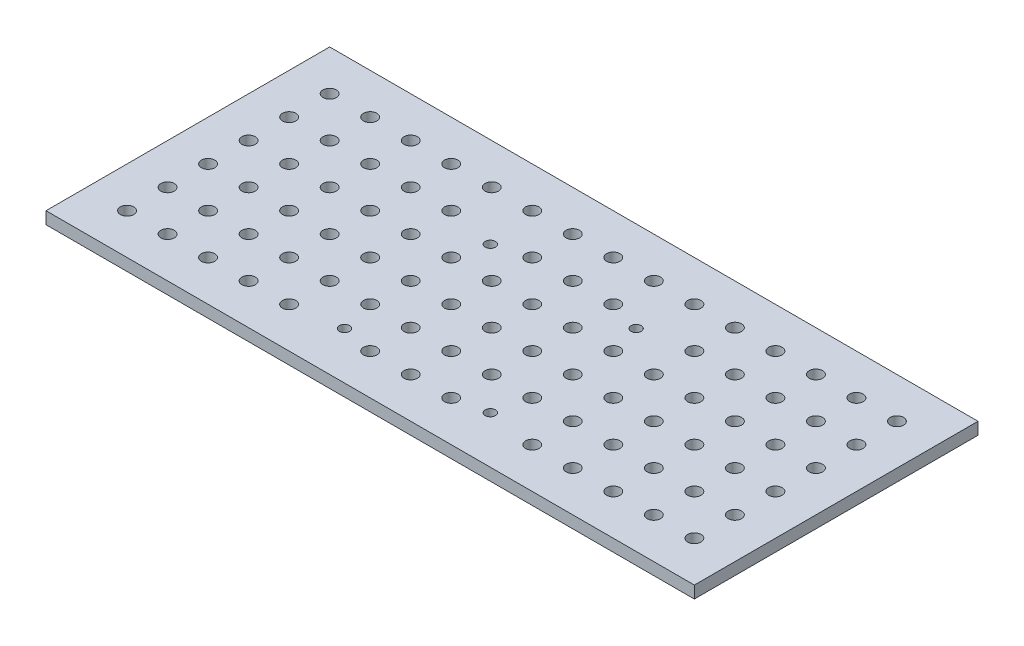
SolidWorks part; units mm, degrees
ref_plane "前视基准面" through (0, 0, 0) normal (0, 0, 1) x (1, 0, 0)
ref_plane "上视基准面" through (0, 0, 0) normal (0, 1, 0) x (1, 0, 0)
ref_plane "右视基准面" through (0, 0, 0) normal (1, 0, 0) x (0, 0, -1)
sketch "草图1" plane through (0, 0, 0) normal (0, 1, 0) x (1, 0, 0)
  line L1 (-80, -35) -> (80, -35)
  line L2 (-80, -35) -> (-80, 35)
  line L3 (-80, 35) -> (80, 35)
  line L4 (80, -35) -> (80, 35)
  line L5 (-80, -35) -> (80, 35) construction
  line L6 (-80, 35) -> (80, -35) construction
  point P0 (0, 0)
  dimension "D1" = 160
  dimension "D2" = 70
extrude "凸台-拉伸1" add sketch "草图1" along normal blind 3 contours L2 L1 L4 L3
sketch "草图2" plane through (0, 3, 0) normal (0, 1, 0) x (1, 0, 0)
  line L0 (-80, 35) -> (80, 35) construction
  line L3 (-80, -35) -> (-80, 35) construction
  circle A0 centre (-70, 25) radius 1.65
  circle A1 centre (-60, 25) radius 1.65
  circle A2 centre (-50, 25) radius 1.65
  circle A3 centre (-40, 25) radius 1.65
  circle A4 centre (-30, 25) radius 1.65
  circle A5 centre (-20, 25) radius 1.65
  circle A6 centre (-10, 25) radius 1.65
  circle A7 centre (0, 25) radius 1.65
  circle A8 centre (10, 25) radius 1.65
  circle A9 centre (20, 25) radius 1.65
  circle A10 centre (30, 25) radius 1.65
  circle A11 centre (40, 25) radius 1.65
  circle A12 centre (50, 25) radius 1.65
  circle A13 centre (60, 25) radius 1.65
  circle A14 centre (70, 25) radius 1.65
  circle A15 centre (-60, 15) radius 1.65
  circle A16 centre (-50, 15) radius 1.65
  circle A17 centre (-40, 15) radius 1.65
  circle A18 centre (-30, 15) radius 1.65
  circle A19 centre (-20, 15) radius 1.65
  circle A20 centre (-10, 15) radius 1.65
  circle A21 centre (0, 15) radius 1.65
  circle A22 centre (10, 15) radius 1.65
  circle A23 centre (20, 15) radius 1.65
  circle A24 centre (30, 15) radius 1.65
  circle A25 centre (40, 15) radius 1.65
  circle A26 centre (50, 15) radius 1.65
  circle A27 centre (60, 15) radius 1.65
  circle A28 centre (70, 15) radius 1.65
  circle A29 centre (-60, 5) radius 1.65
  circle A30 centre (-50, 5) radius 1.65
  circle A31 centre (-40, 5) radius 1.65
  circle A32 centre (-30, 5) radius 1.65
  circle A33 centre (-20, 5) radius 1.65
  circle A34 centre (-10, 5) radius 1.65
  circle A35 centre (0, 5) radius 1.65
  circle A36 centre (10, 5) radius 1.65
  circle A37 centre (20, 5) radius 1.65
  circle A38 centre (30, 5) radius 1.65
  circle A39 centre (40, 5) radius 1.65
  circle A40 centre (50, 5) radius 1.65
  circle A41 centre (60, 5) radius 1.65
  circle A42 centre (70, 5) radius 1.65
  circle A43 centre (-60, -5) radius 1.65
  circle A44 centre (-50, -5) radius 1.65
  circle A45 centre (-40, -5) radius 1.65
  circle A46 centre (-30, -5) radius 1.65
  circle A47 centre (-20, -5) radius 1.65
  circle A48 centre (-10, -5) radius 1.65
  circle A49 centre (0, -5) radius 1.65
  circle A50 centre (10, -5) radius 1.65
  circle A51 centre (20, -5) radius 1.65
  circle A52 centre (30, -5) radius 1.65
  circle A53 centre (40, -5) radius 1.65
  circle A54 centre (50, -5) radius 1.65
  circle A55 centre (60, -5) radius 1.65
  circle A56 centre (70, -5) radius 1.65
  circle A57 centre (-60, -15) radius 1.65
  circle A58 centre (-50, -15) radius 1.65
  circle A59 centre (-40, -15) radius 1.65
  circle A60 centre (-30, -15) radius 1.65
  circle A61 centre (-20, -15) radius 1.65
  circle A62 centre (-10, -15) radius 1.65
  circle A63 centre (0, -15) radius 1.65
  circle A64 centre (10, -15) radius 1.65
  circle A65 centre (20, -15) radius 1.65
  circle A66 centre (30, -15) radius 1.65
  circle A67 centre (40, -15) radius 1.65
  circle A68 centre (50, -15) radius 1.65
  circle A69 centre (60, -15) radius 1.65
  circle A70 centre (70, -15) radius 1.65
  circle A71 centre (-60, -25) radius 1.65
  circle A72 centre (-50, -25) radius 1.65
  circle A73 centre (-40, -25) radius 1.65
  circle A74 centre (-30, -25) radius 1.65
  circle A75 centre (-20, -25) radius 1.65
  circle A76 centre (-10, -25) radius 1.65
  circle A77 centre (0, -25) radius 1.65
  circle A78 centre (10, -25) radius 1.65
  circle A79 centre (20, -25) radius 1.65
  circle A80 centre (30, -25) radius 1.65
  circle A81 centre (40, -25) radius 1.65
  circle A82 centre (50, -25) radius 1.65
  circle A83 centre (60, -25) radius 1.65
  circle A84 centre (70, -25) radius 1.65
  circle A85 centre (-70, 15) radius 1.65
  circle A86 centre (-70, 5) radius 1.65
  circle A87 centre (-70, -5) radius 1.65
  circle A88 centre (-70, -15) radius 1.65
  circle A89 centre (-70, -25) radius 1.65
  dimension "D1" = 3.3
  dimension "D2" = 10
  dimension "D3" = 10
  dimension "D4" = 15
  dimension "D5" = 6
extrude "切除-拉伸1" cut sketch "草图2" against normal blind 3
sketch "草图3" plane through (0, 3, 0) normal (0, 1, 0) x (1, 0, 0)
  line L5 (-17.5, -22.5896) -> (17.5, 12.4104) construction
  circle A0 centre (-20, 15) radius 1.65
  circle A1 centre (20, 15) radius 1.65
  circle A2 centre (20, -25) radius 1.65
  circle A3 centre (-20, -25) radius 1.65
  point P0 (0, -5.0896)
extrude "凸台-拉伸2" add sketch "草图3" against normal blind 3
sketch "草图4" plane through (0, 3, 0) normal (0, 1, 0) x (1, 0, 0)
  line L5 (-18, 12.65) -> (18, 12.65)
  line L7 (-18, 12.65) -> (-18, -23.35)
  line L8 (-18, -23.35) -> (18, -23.35)
  line L9 (18, 12.65) -> (18, -23.35)
  line L10 (-18, 12.65) -> (18, -23.35) construction
  line L11 (-18, -23.35) -> (18, 12.65) construction
  circle A0 centre (18, 12.65) radius 1.25
  circle A1 centre (-18, 12.65) radius 1.25
  circle A2 centre (18, -23.35) radius 1.25
  circle A3 centre (-18, -23.35) radius 1.25
  circle A5 centre (0, -25) radius 1.65 construction
  point P12 (0, -5.35)
  dimension "D3" = 36
  dimension "D1" = 2.5
  dimension "D2" = 36
extrude "切除-拉伸2" cut sketch "草图4" against normal blind 3 contours L7 A1 L5 | L5 A1 L7 | L9 A0 L5 | L5 A0 L9 | L8 A2 L9 | L9 A2 L8 | L8 A3 L7 | L7 A3 L8
